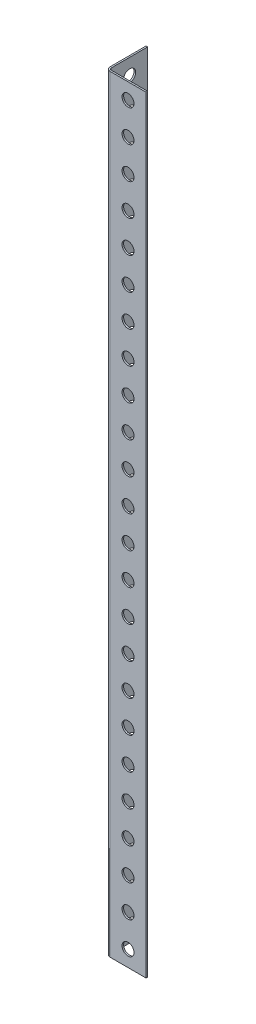
SolidWorks part; units mm, degrees
material "AISI 1020"
ref_plane "Front Plane" through (0, 0, 0) normal (0, 0, 1) x (1, 0, 0)
ref_plane "Top Plane" through (0, 0, 0) normal (0, 1, 0) x (1, 0, 0)
ref_plane "Right Plane" through (0, 0, 0) normal (1, 0, 0) x (0, 0, -1)
sketch "Sketch1" plane through (0, 0, 0) normal (0, 1, 0) x (1, 0, 0)
  line L0 (1.27, 30.48) -> (30.48, 30.48)
  line L1 (0, 0) -> (31.75, 0)
  line L2 (0, 0) -> (0, 31.75)
  line L3 (0, 31.75) -> (31.75, 31.75)
  line L4 (31.75, 0) -> (31.75, 31.75)
  line L5 (30.48, 1.27) -> (30.48, 30.48)
  line L6 (1.27, 1.27) -> (30.48, 1.27)
  line L7 (1.27, 1.27) -> (1.27, 30.48)
  line L8 (1.27, 30.48) -> (1.27, 31.75)
  line L9 (30.48, 1.27) -> (31.75, 1.27)
  dimension "D1" = 31.75
  dimension "D2" = 31.75
  dimension "D3" = 1.27
extrude "Boss-Extrude1" add sketch "Sketch1" along normal blind 1219.2 contours L9 L6 L7 L8 L3 L2 L1 L4
sketch "Sketch3" plane through (0, 0, 0) normal (-1, 0, 0) x (0, 0, 1)
  line L0 (-17.4625, 0) -> (-17.4625, 12.7) construction
  line L2 (-31.75, 1219.2) -> (-31.75, 0) construction
  circle A0 centre (-17.4625, 12.7) radius 4.7625
  circle A1 centre (-17.4625, 38.1) radius 4.7625
  circle A2 centre (-17.4625, 63.5) radius 4.7625
  circle A3 centre (-17.4625, 88.9) radius 4.7625
  circle A4 centre (-17.4625, 114.3) radius 4.7625
  circle A5 centre (-17.4625, 139.7) radius 4.7625
  circle A6 centre (-17.4625, 165.1) radius 4.7625
  circle A7 centre (-17.4625, 190.5) radius 4.7625
  circle A8 centre (-17.4625, 215.9) radius 4.7625
  circle A9 centre (-17.4625, 241.3) radius 4.7625
  circle A10 centre (-17.4625, 266.7) radius 4.7625
  circle A11 centre (-17.4625, 292.1) radius 4.7625
  circle A12 centre (-17.4625, 317.5) radius 4.7625
  circle A13 centre (-17.4625, 342.9) radius 4.7625
  circle A14 centre (-17.4625, 368.3) radius 4.7625
  circle A15 centre (-17.4625, 393.7) radius 4.7625
  circle A16 centre (-17.4625, 419.1) radius 4.7625
  circle A17 centre (-17.4625, 444.5) radius 4.7625
  circle A18 centre (-17.4625, 469.9) radius 4.7625
  circle A19 centre (-17.4625, 495.3) radius 4.7625
  circle A20 centre (-17.4625, 520.7) radius 4.7625
  circle A21 centre (-17.4625, 546.1) radius 4.7625
  circle A22 centre (-17.4625, 571.5) radius 4.7625
  circle A23 centre (-17.4625, 596.9) radius 4.7625
  circle A24 centre (-17.4625, 622.3) radius 4.7625
  circle A25 centre (-17.4625, 647.7) radius 4.7625
  circle A26 centre (-17.4625, 673.1) radius 4.7625
  circle A27 centre (-17.4625, 698.5) radius 4.7625
  circle A28 centre (-17.4625, 723.9) radius 4.7625
  circle A29 centre (-17.4625, 749.3) radius 4.7625
  circle A30 centre (-17.4625, 774.7) radius 4.7625
  circle A31 centre (-17.4625, 800.1) radius 4.7625
  circle A32 centre (-17.4625, 825.5) radius 4.7625
  circle A33 centre (-17.4625, 850.9) radius 4.7625
  circle A34 centre (-17.4625, 876.3) radius 4.7625
  circle A35 centre (-17.4625, 901.7) radius 4.7625
  circle A36 centre (-17.4625, 927.1) radius 4.7625
  circle A37 centre (-17.4625, 952.5) radius 4.7625
  circle A38 centre (-17.4625, 977.9) radius 4.7625
  circle A39 centre (-17.4625, 1003.3) radius 4.7625
  circle A40 centre (-17.4625, 1028.7) radius 4.7625
  circle A41 centre (-17.4625, 1054.1) radius 4.7625
  circle A42 centre (-17.4625, 1079.5) radius 4.7625
  circle A43 centre (-17.4625, 1104.9) radius 4.7625
  circle A44 centre (-17.4625, 1130.3) radius 4.7625
  circle A45 centre (-17.4625, 1155.7) radius 4.7625
  circle A46 centre (-17.4625, 1181.1) radius 4.7625
  circle A47 centre (-17.4625, 1206.5) radius 4.7625
  dimension "D1" = 9.525
  dimension "D2" = 12.7
  dimension "D4" = 14.2875
  dimension "D3" = 48
extrude "Cut-Extrude1" cut sketch "Sketch3" against normal up to next (1.27 mm away)
sketch "Sketch4" plane through (0, 0, 0) normal (0, 0, 1) x (1, 0, 0)
  line L0 (17.4625, 1219.2) -> (17.4625, 1206.5) construction
  line L2 (31.75, 1219.2) -> (31.75, 0) construction
  circle A0 centre (17.4625, 1206.5) radius 4.7625
  circle A1 centre (17.4625, 1181.1) radius 4.7625
  circle A2 centre (17.4625, 1155.7) radius 4.7625
  circle A3 centre (17.4625, 1130.3) radius 4.7625
  circle A4 centre (17.4625, 1104.9) radius 4.7625
  circle A5 centre (17.4625, 1079.5) radius 4.7625
  circle A6 centre (17.4625, 1054.1) radius 4.7625
  circle A7 centre (17.4625, 1028.7) radius 4.7625
  circle A8 centre (17.4625, 1003.3) radius 4.7625
  circle A9 centre (17.4625, 977.9) radius 4.7625
  circle A10 centre (17.4625, 952.5) radius 4.7625
  circle A11 centre (17.4625, 927.1) radius 4.7625
  circle A12 centre (17.4625, 901.7) radius 4.7625
  circle A13 centre (17.4625, 876.3) radius 4.7625
  circle A14 centre (17.4625, 850.9) radius 4.7625
  circle A15 centre (17.4625, 825.5) radius 4.7625
  circle A16 centre (17.4625, 800.1) radius 4.7625
  circle A17 centre (17.4625, 774.7) radius 4.7625
  circle A18 centre (17.4625, 749.3) radius 4.7625
  circle A19 centre (17.4625, 723.9) radius 4.7625
  circle A20 centre (17.4625, 698.5) radius 4.7625
  circle A21 centre (17.4625, 673.1) radius 4.7625
  circle A22 centre (17.4625, 647.7) radius 4.7625
  circle A23 centre (17.4625, 622.3) radius 4.7625
  circle A24 centre (17.4625, 596.9) radius 4.7625
  circle A25 centre (17.4625, 571.5) radius 4.7625
  circle A26 centre (17.4625, 546.1) radius 4.7625
  circle A27 centre (17.4625, 520.7) radius 4.7625
  circle A28 centre (17.4625, 495.3) radius 4.7625
  circle A29 centre (17.4625, 469.9) radius 4.7625
  circle A30 centre (17.4625, 444.5) radius 4.7625
  circle A31 centre (17.4625, 419.1) radius 4.7625
  circle A32 centre (17.4625, 393.7) radius 4.7625
  circle A33 centre (17.4625, 368.3) radius 4.7625
  circle A34 centre (17.4625, 342.9) radius 4.7625
  circle A35 centre (17.4625, 317.5) radius 4.7625
  circle A36 centre (17.4625, 292.1) radius 4.7625
  circle A37 centre (17.4625, 266.7) radius 4.7625
  circle A38 centre (17.4625, 241.3) radius 4.7625
  circle A39 centre (17.4625, 215.9) radius 4.7625
  circle A40 centre (17.4625, 190.5) radius 4.7625
  circle A41 centre (17.4625, 165.1) radius 4.7625
  circle A42 centre (17.4625, 139.7) radius 4.7625
  circle A43 centre (17.4625, 114.3) radius 4.7625
  circle A44 centre (17.4625, 88.9) radius 4.7625
  circle A45 centre (17.4625, 63.5) radius 4.7625
  circle A46 centre (17.4625, 38.1) radius 4.7625
  circle A47 centre (17.4625, 12.7) radius 4.7625
  dimension "D1" = 9.525
  dimension "D2" = 12.7
  dimension "D4" = 14.2875
  dimension "D3" = 48
extrude "Cut-Extrude2" cut sketch "Sketch4" against normal up to next (1.27 mm away)
fillet "Fillet1" radius 3.175 1 edges at (0, 609.6, 0)
fillet "Fillet2" radius 1.5875 1 edges at (1.27, 609.6, -1.27)
sketch "Sketch5" plane through (0, 1219.2, 0) normal (0, 1, 0) x (1, 0, 0)
  line L12 (0, 31.75) -> (0, 3.175)
  line L13 (3.175, 0) -> (31.75, 0)
  line L14 (31.75, 0) -> (31.75, 1.27)
  line L15 (31.75, 1.27) -> (2.8575, 1.27)
  line L16 (1.27, 2.8575) -> (1.27, 31.75)
  line L17 (1.27, 31.75) -> (0, 31.75)
  line L18 (0, 31.75) -> (0, 3.175)
  line L19 (3.175, 0) -> (31.75, 0)
  line L20 (31.75, 0) -> (31.75, 1.27)
  line L21 (31.75, 1.27) -> (2.8575, 1.27)
  line L22 (1.27, 2.8575) -> (1.27, 31.75)
  line L23 (1.27, 31.75) -> (0, 31.75)
  arc A4 (0, 3.175) -> (3.175, 0) centre (3.175, 3.175) ccw
  arc A5 (1.27, 2.8575) -> (2.8575, 1.27) centre (2.8575, 2.8575) ccw
  arc A6 (0, 3.175) -> (3.175, 0) centre (3.175, 3.175) ccw
  arc A7 (1.27, 2.8575) -> (2.8575, 1.27) centre (2.8575, 2.8575) ccw
  dimension "D1" = 0
extrude "Cut-Extrude3" cut sketch "Sketch5" against normal blind 609.6
